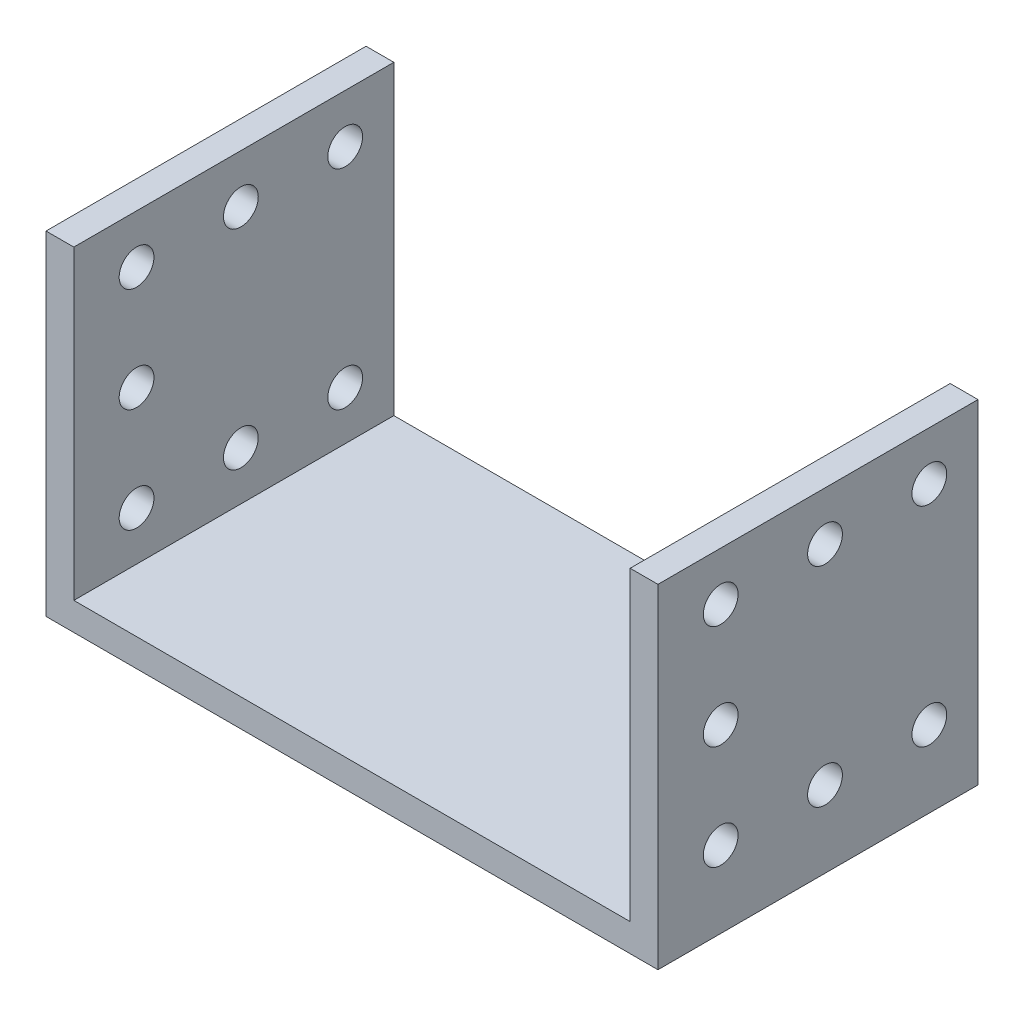
SolidWorks part; units mm, degrees
ref_plane "前视基准面" through (0, 0, 0) normal (0, 0, 1) x (1, 0, 0)
ref_plane "上视基准面" through (0, 0, 0) normal (0, 1, 0) x (1, 0, 0)
ref_plane "右视基准面" through (0, 0, 0) normal (1, 0, 0) x (0, 0, -1)
sketch "草图1" plane through (0, 0, 0) normal (0, 0, 1) x (1, 0, 0)
  line L0 (-22, 0) -> (22, 0)
  line L1 (0, 0) -> (0, 32.9346) construction
  line L2 (-22, 0) -> (-22, 24)
  line L3 (-22, 24) -> (-20, 24)
  line L4 (-20, 24) -> (-20, 2)
  line L5 (-20, 2) -> (20, 2)
  line L6 (22, 0) -> (22, 24)
  line L7 (22, 24) -> (20, 24)
  line L8 (20, 24) -> (20, 2)
  point P4 (0, 0)
  dimension "D1" = 40
  dimension "D2" = 22
  dimension "D3" = 2
  dimension "D4" = 2
extrude "凸台-拉伸1" add sketch "草图1" along normal blind 32
sketch "草图3" plane through (22, 0, 0) normal (1, 0, 0) x (0, 0, -1)
  line L0 (0, 13) -> (-37.9638, 13) construction
  line L1 (0, 0) -> (0, 24) construction
  line L2 (-3.5, 20.5) -> (-18.5, 20.5) construction
  line L3 (-3.5, 20.5) -> (-3.5, 13) construction
  line L4 (-32, 24) -> (0, 24) construction
  line L5 (-18.5, 20.5) -> (-18.5, 13) construction
  circle A0 centre (-3.5, 20.5) radius 1.25
  circle A1 centre (-18.5, 20.5) radius 1.25
  circle A2 centre (-11, 20.5) radius 1.25
  circle A3 centre (-3.5, 5.5) radius 1.25
  circle A4 centre (-11, 5.5) radius 1.25
  circle A5 centre (-18.5, 5.5) radius 1.25
  circle A7 centre (-18.5, 13) radius 1.25
  dimension "D4" = 2.5
  dimension "D1" = 3.5
  dimension "D2" = 3.5
  dimension "D3" = 15
  dimension "D5" = 11
extrude "切除-拉伸2" cut sketch "草图3" against normal through all
sketch "草图5" plane through (0, 2, 0) normal (0, 1, 0) x (1, 0, 0)
  line L0 (0, 0) -> (0, -32) construction
  line L1 (20, -32) -> (-20, -32) construction
  circle A0 centre (-15, -27) radius 2.2
  circle A1 centre (15, -27) radius 2.2
  dimension "D3" = 4.4
  dimension "D1" = 30
  dimension "D2" = 5
extrude "切除-拉伸3" cut sketch "草图5" against normal through all
sketch "草图6" plane through (22, 0, 0) normal (1, 0, 0) x (0, 0, -1)
  line L0 (-23.0113, 24) -> (-23.0113, 0)
  line L1 (-32, 24) -> (0, 24) construction
  line L2 (-32, 0) -> (0, 0) construction
  line L3 (-32, 24) -> (-32, 0)
  line L4 (-32, 0) -> (-23.0113, 0)
  line L5 (-32, 24) -> (-23.0113, 24)
extrude "切除-拉伸4" cut sketch "草图6" against normal through all
